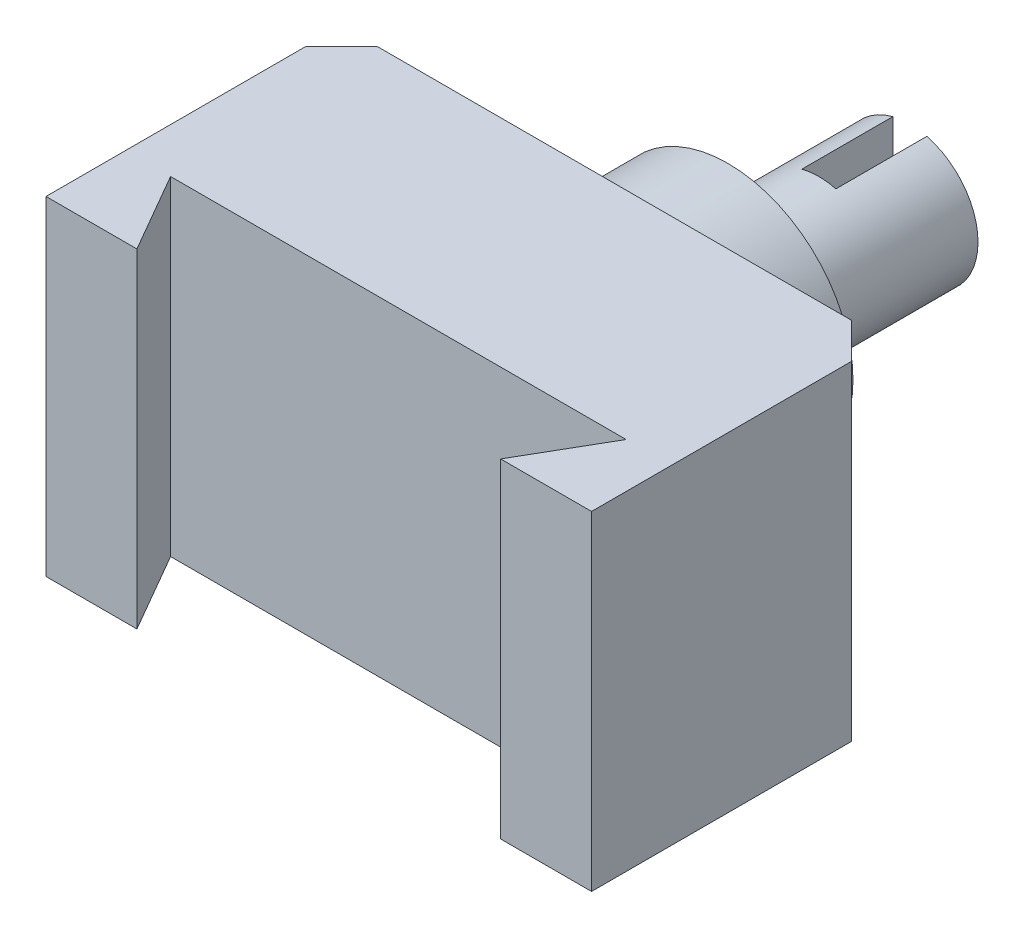
SolidWorks part; units mm, degrees
ref_plane "Front Plane" through (0, 0, 0) normal (0, 0, 1) x (1, 0, 0)
ref_plane "Top Plane" through (0, 0, 0) normal (0, 1, 0) x (1, 0, 0)
ref_plane "Right Plane" through (0, 0, 0) normal (1, 0, 0) x (0, 0, -1)
sketch "Sketch1" plane through (0, 0, 0) normal (0, 1, 0) x (1, 0, 0)
  line L0 (-50.8, -41.275) -> (-63.6316, -19.05)
  line L1 (-76.2, -41.275) -> (-50.8, -41.275)
  line L2 (-76.2, -41.275) -> (-76.2, 41.275)
  line L3 (-76.2, 41.275) -> (76.2, 41.275)
  line L4 (76.2, -41.275) -> (76.2, 41.275)
  line L5 (-76.2, -41.275) -> (76.2, 41.275) construction
  line L6 (-76.2, 41.275) -> (76.2, -41.275) construction
  line L7 (-63.6316, -19.05) -> (63.6316, -19.05)
  line L8 (63.6316, -19.05) -> (50.8, -41.275)
  line L9 (0, 41.275) -> (0, -41.275) construction
  line L10 (50.8, -41.275) -> (76.2, -41.275)
  point P0 (0, 0)
  point P12 (0, 0)
  point P13 (-228.0397, 7.4239)
  dimension "D1" = 152.4
  dimension "D2" = 82.55
  dimension "D4" = 22.225
  dimension "D5" = 101.6
  dimension "D6" = 60
extrude "Boss-Extrude1" add sketch "Sketch1" along normal mid plane 91.948
sketch "Sketch2" plane through (0, 0, -41.275) normal (0, 0, -1) x (-1, 0, 0)
  circle A0 centre (0, 0) radius 34.925
  dimension "D1" = 69.85
extrude "Boss-Extrude2" add sketch "Sketch2" along normal blind 31.75
sketch "Sketch3" plane through (0, 0, -73.025) normal (0, 0, -1) x (-1, 0, 0)
  circle A0 centre (0, 0) radius 19.05
  dimension "D1" = 38.1
extrude "Boss-Extrude3" add sketch "Sketch3" along normal blind 50.8
sketch "Sketch4" plane through (0, 0, -123.825) normal (0, 0, -1) x (-1, 0, 0)
  line L0 (-4.7625, 18.4451) -> (-4.7625, -18.4451)
  line L1 (4.7625, 18.4451) -> (4.7625, -18.4451)
  line L2 (0, 0) -> (0, 19.05) construction
  arc A0 (4.7625, 18.4451) -> (-4.7625, 18.4451) centre (0, 0) ccw
  circle A1 centre (0, 0) radius 19.05
  arc A2 (-4.7625, -18.4451) -> (4.7625, -18.4451) centre (0, 0) ccw
  dimension "D2" = 9.525
  dimension "D1" = 0
extrude "Cut-Extrude1" cut sketch "Sketch4" against normal blind 25.4
chamfer "Chamfer1" distance 10 angle 45 2 edges at (-76.2, 0, -41.275) (76.2, 0, -41.275)
